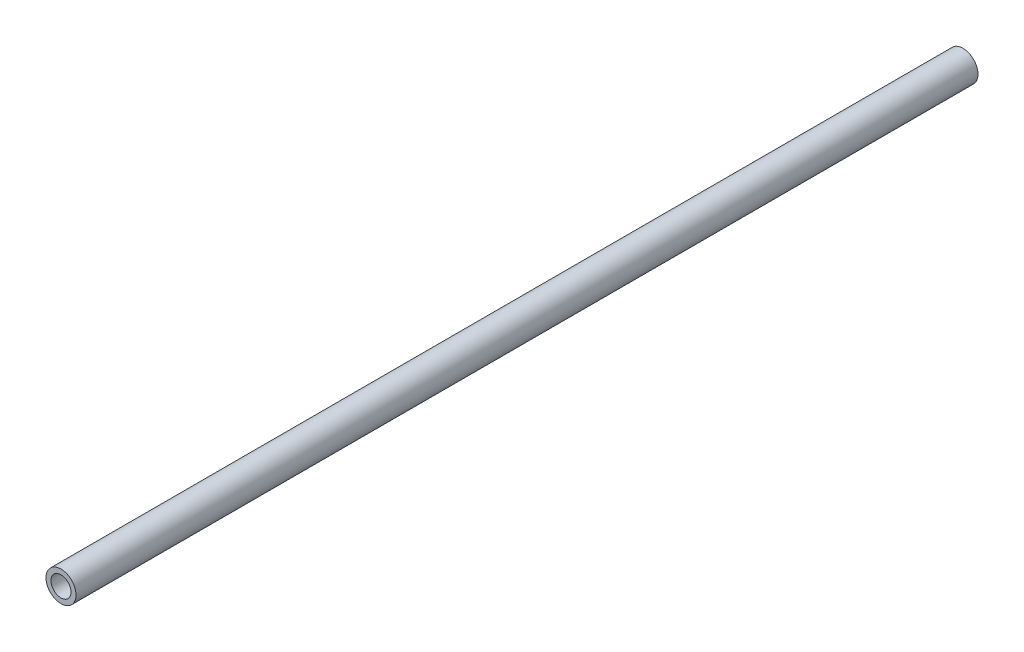
SolidWorks part; units mm, degrees
ref_plane "Front Plane" through (0, 0, 0) normal (0, 0, 1) x (1, 0, 0)
ref_plane "Top Plane" through (0, 0, 0) normal (0, 1, 0) x (1, 0, 0)
ref_plane "Right Plane" through (0, 0, 0) normal (1, 0, 0) x (0, 0, -1)
sketch "Sketch1" plane through (0, 0, 0) normal (0, 0, 1) x (1, 0, 0)
  circle A0 centre (0, 0) radius 3
  circle A1 centre (0, 0) radius 2
  dimension "D1" = 4
  dimension "D2" = 6
extrude "Boss-Extrude1" add sketch "Sketch1" along normal blind 180.18
